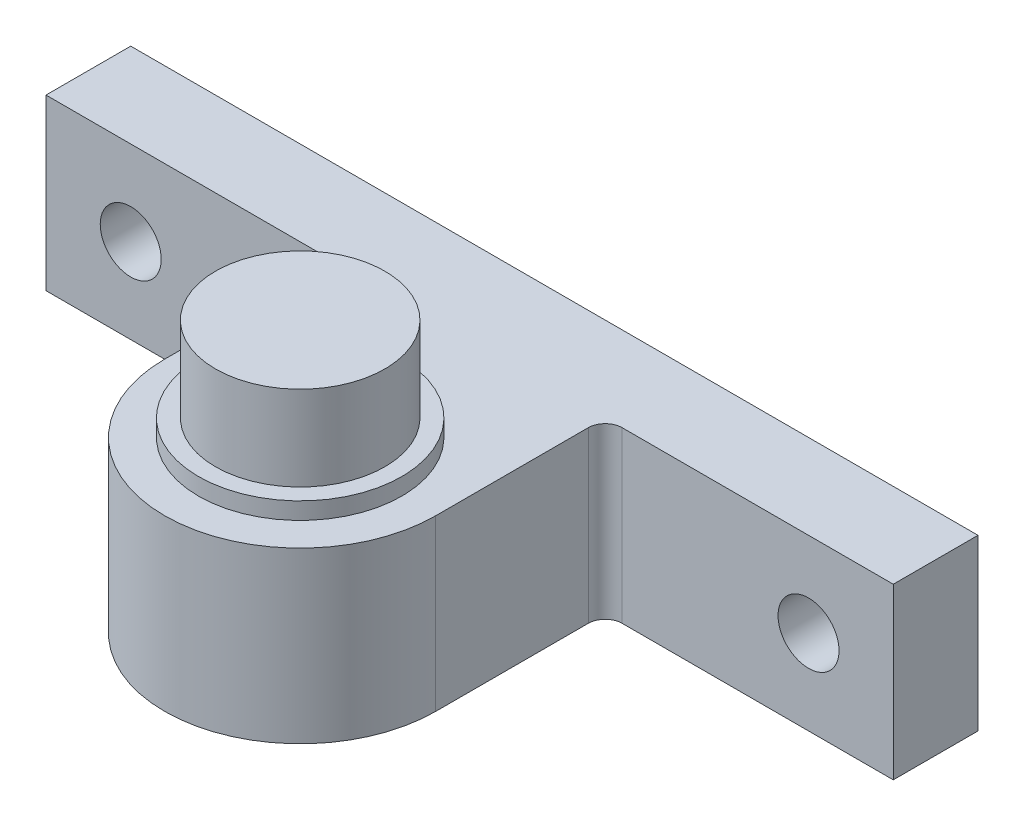
SolidWorks part; units mm, degrees
ref_plane "正面" through (0, 0, 0) normal (0, 0, 1) x (1, 0, 0)
ref_plane "平面" through (0, 0, 0) normal (0, 1, 0) x (1, 0, 0)
ref_plane "右側面" through (0, 0, 0) normal (1, 0, 0) x (0, 0, -1)
sketch "ｽｹｯﾁ1" plane through (0, 0, 0) normal (0, 1, 0) x (1, 0, 0)
  line L0 (-25.8461, 0) -> (29.9033, 0) construction
  line L1 (0, 18.6332) -> (0, -16.2289) construction
  line L2 (-8, 0) -> (-8, 10)
  line L7 (-8, 10) -> (-25, 10)
  line L8 (8, 0) -> (8, 10)
  line L10 (-25, 10) -> (-25, 15)
  line L11 (-25, 15) -> (25, 15)
  line L12 (25, 10) -> (25, 15)
  line L17 (8, 10) -> (25, 10)
  arc A0 (8, 0) -> (-8, 0) centre (0, 0) cw
  dimension "D1" = 8
  dimension "D5" = 15
extrude "ﾎﾞｽ - 押し出し1" add sketch "ｽｹｯﾁ1" along normal blind 10
sketch "ｽｹｯﾁ2" plane through (0, 10, 0) normal (0, 1, 0) x (1, 0, 0)
  circle A0 centre (0, 0) radius 5
  dimension "D1" = 10
extrude "ﾎﾞｽ - 押し出し2" add sketch "ｽｹｯﾁ2" along normal blind 6
sketch "ｽｹｯﾁ3" plane through (0, 10, 0) normal (0, 1, 0) x (1, 0, 0)
  circle A0 centre (0, 0) radius 6
extrude "ﾎﾞｽ - 押し出し3" add sketch "ｽｹｯﾁ3" along normal blind 1
sketch "ｽｹｯﾁ4" plane through (0, 0, -15) normal (0, 0, -1) x (-1, 0, 0)
  line L0 (0, 0) -> (0, 10) construction
  line L1 (25, 10) -> (-25, 10) construction
  line L2 (0, 10) -> (0, 5) construction
  line L3 (0, 5) -> (25, 5) construction
  line L4 (25, 10) -> (25, 0) construction
  line L5 (25, 5) -> (-25, 5) construction
  line L6 (-25, 10) -> (-25, 0) construction
  circle A0 centre (20, 5) radius 1.8
  circle A1 centre (-20, 5) radius 1.8
  dimension "D1" = 3.6
  dimension "D2" = 20
  dimension "D3" = 20
extrude "ｶｯﾄ - 押し出し1" cut sketch "ｽｹｯﾁ4" against normal through all
fillet "ﾌｨﾚｯﾄ1" radius 1 2 edges at (-8, 5, -10) (8, 5, -10)
